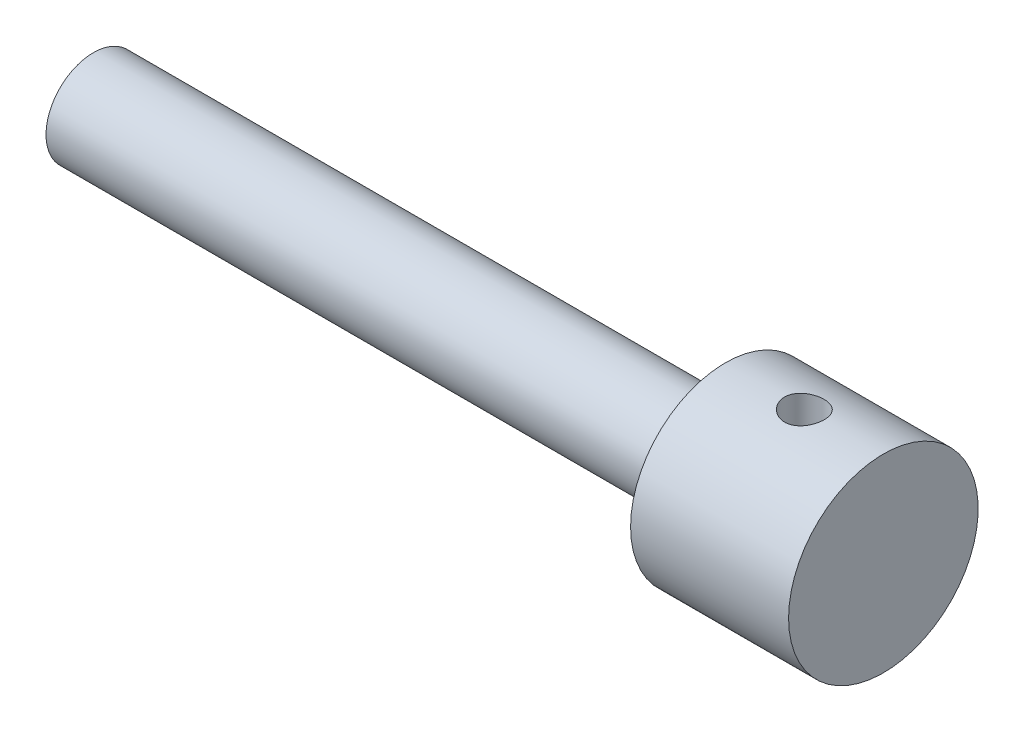
SolidWorks part; units mm, degrees
ref_plane "정면" through (0, 0, 0) normal (0, 0, 1) x (1, 0, 0)
ref_plane "윗면" through (0, 0, 0) normal (0, 1, 0) x (1, 0, 0)
ref_plane "우측면" through (0, 0, 0) normal (1, 0, 0) x (0, 0, -1)
sketch "스케치1" plane through (0, 0, 0) normal (0, 0, 1) x (1, 0, 0)
  line L0 (0, 0) -> (100, 0) construction
  line L1 (0, 0) -> (0, 6)
  line L2 (0, 6) -> (80, 6)
  line L3 (80, 6) -> (80, 12)
  line L4 (80, 12) -> (100, 12)
  line L5 (100, 12) -> (100, 0)
  line L6 (0, 0) -> (100, 0)
  point P3 (73.8764, 14.4663)
  dimension "D1" = 100
  dimension "D2" = 20
  dimension "D3" = 24
  dimension "D4" = 12
revolve "회전1" add sketch "스케치1" angle 360 about L0
hole_wizard "Ø5.0 (5) 지름 구멍1" positions "3D스케치1" profile "스케치2" hole size "Ø5.0" standard "KS" end condition through all
sketch3d "3D스케치1"
  point P0 (90, -12, 0)
  point P6 (-101.4867, 106.473, 0)
  dimension "D1" = 10
sketch "스케치2" plane through (90, -12, 0) normal (1, 0, 0) x (0, 0, -1)
  line L0 (0, 0) -> (0, 24)
  line L1 (0, 24) -> (2.5, 24)
  line L2 (2.5, 24) -> (2.5, 0)
  line L5 (2.5, 0) -> (0, 0)
  line L11 (0, -6.35) -> (0, 107.95) construction
  dimension "관통 구멍 지름" = 5
  dimension "관통 구멍 깊이" = 24
